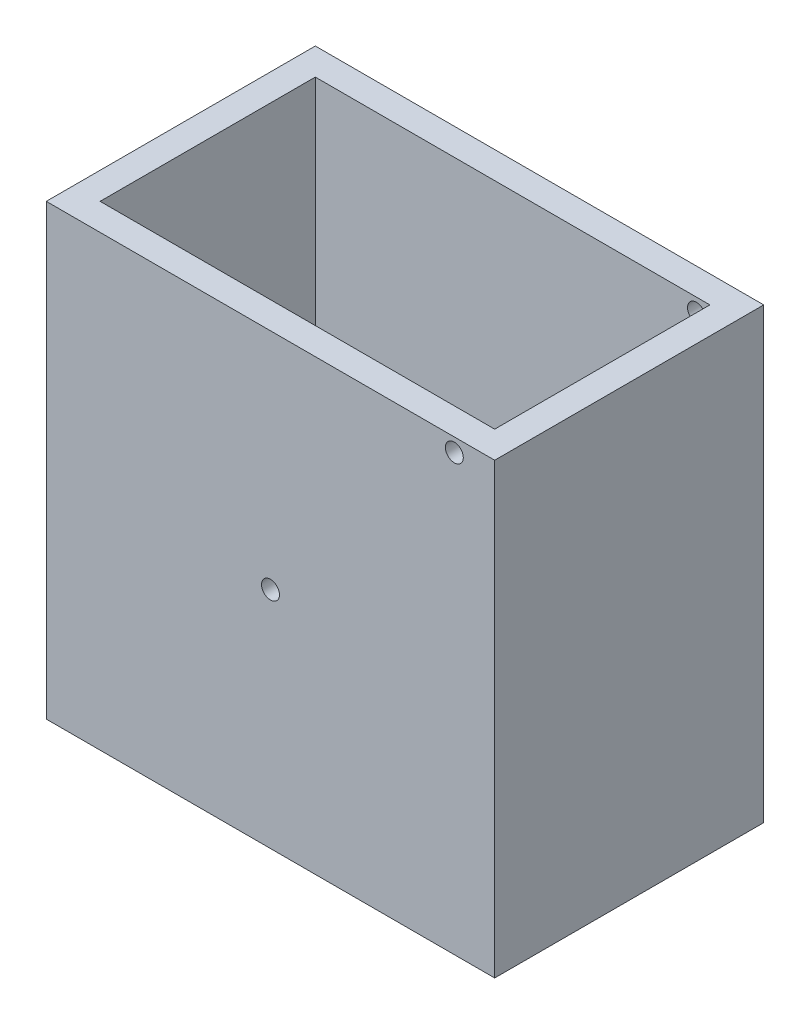
SolidWorks part; units mm, degrees
ref_plane "Front Plane" through (0, 0, 0) normal (0, 0, 1) x (1, 0, 0)
ref_plane "Top Plane" through (0, 0, 0) normal (0, 1, 0) x (1, 0, 0)
ref_plane "Right Plane" through (0, 0, 0) normal (1, 0, 0) x (0, 0, -1)
sketch "Sketch1" plane through (0, 0, 0) normal (0, 0, 1) x (1, 0, 0)
  line L1 (0, 0) -> (250, 0)
  line L2 (0, 0) -> (0, -250)
  line L3 (0, -250) -> (250, -250)
  line L4 (250, 0) -> (250, -250)
  dimension "D1" = 250
  dimension "D2" = 250
extrude "Boss-Extrude1" add sketch "Sketch1" along normal blind 150
sketch "Sketch2" plane through (0, 0, 0) normal (0, 1, 0) x (1, 0, 0)
  line L0 (250, 0) -> (0, 0) construction
  line L1 (235, -135) -> (15, -135)
  line L2 (235, -135) -> (235, -15)
  line L3 (235, -15) -> (15, -15)
  line L4 (15, -135) -> (15, -15)
  line L5 (235, -135) -> (15, -15) construction
  line L6 (235, -15) -> (15, -135) construction
  line L7 (250, -150) -> (0, -150) construction
  line L8 (250, -150) -> (250, 0) construction
  line L9 (0, -150) -> (0, 0) construction
  point P0 (125, -75)
  dimension "D1" = 15
  dimension "D2" = 15
  dimension "D3" = 15
  dimension "D4" = 15
extrude "Cut-Extrude1" cut sketch "Sketch2" against normal blind 235
sketch "Sketch3" plane through (0, 0, 150) normal (0, 0, 1) x (1, 0, 0)
  circle A0 centre (125, -125) radius 5
  circle A2 centre (227.5, -7.5) radius 5
  dimension "D1" = 10
extrude "Cut-Extrude5" cut sketch "Sketch3" against normal blind 235
